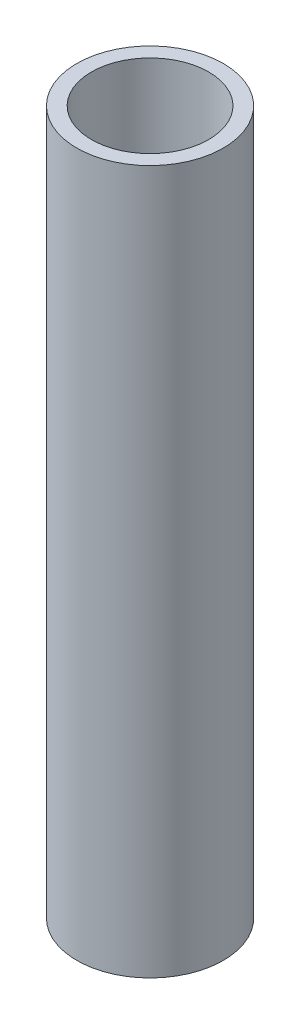
SolidWorks part; units mm, degrees
ref_plane "Front Plane" through (0, 0, 0) normal (0, 0, 1) x (1, 0, 0)
ref_plane "Top Plane" through (0, 0, 0) normal (0, 1, 0) x (1, 0, 0)
ref_plane "Right Plane" through (0, 0, 0) normal (1, 0, 0) x (0, 0, -1)
sketch "Sketch2" plane through (0, 0, 0) normal (0, 1, 0) x (1, 0, 0)
  circle A0 centre (0, 0) radius 7.9375
  circle A1 centre (0, 0) radius 6.35
  dimension "D1" = 12.7
  dimension "D2" = 15.875
extrude "Boss-Extrude1" add sketch "Sketch2" along normal blind 76.2
